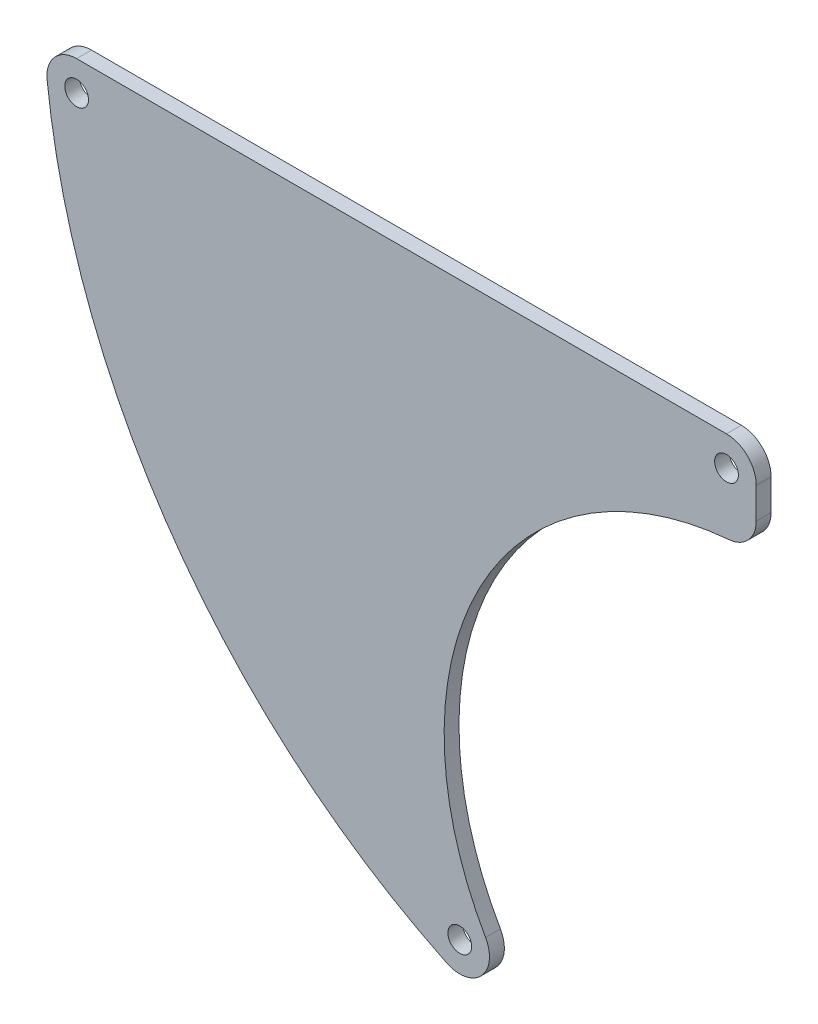
SolidWorks part; units mm, degrees
material "Плата системы питания"
ref_plane "Спереди" through (0, 0, 0) normal (0, 0, 1) x (1, 0, 0)
ref_plane "Сверху" through (0, 0, 0) normal (0, 1, 0) x (1, 0, 0)
ref_plane "Справа" through (0, 0, 0) normal (1, 0, 0) x (0, 0, -1)
sketch "Эскиз1" plane through (0, 0, 0) normal (0, 0, 1) x (1, 0, 0)
  line L1 (0, 0) -> (0, 50000) construction
  line L2 (0, 40.9129) -> (0, 43)
  line L3 (-2, 45) -> (-45.7275, 45)
  arc A0 (-47.7156, 42.7826) -> (-20.8146, 4.7478) centre (0, 48) ccw
  arc A1 (-1.8261, 38.9205) -> (-18.2128, 7.5457) centre (0, 18) ccw
  arc A2 (-20.8146, 4.7478) -> (-18.2128, 7.5457) centre (-19.9474, 6.55) ccw
  circle A7 centre (-19.9474, 6.55) radius 0.8
  arc A8 (-47.7156, 42.7826) -> (-45.7275, 45) centre (-45.7275, 43) cw
  arc A9 (0, 43) -> (-2, 45) centre (-2, 43) ccw
  arc A10 (0, 40.9129) -> (-1.8261, 38.9205) centre (-2, 40.9129) cw
  circle A11 centre (-45.7275, 43) radius 0.8
  circle A12 centre (-2, 43) radius 0.8
  point P10 (0, 40)
  point P17 (0, 45)
  point P20 (0, 39)
  point P23 (0, 0)
  dimension "D1" = 96
  dimension "D2" = 42
  dimension "D4" = 2
  dimension "D5" = 45
  dimension "D6" = 2
  dimension "D7" = 1.6
  dimension "D8" = 1.6
  dimension "D9" = 1.6
  dimension "D3" = 30
  dimension "D10" = 40
extrude "Бобышка-Вытянуть1" add sketch "Эскиз1" along normal blind 1
